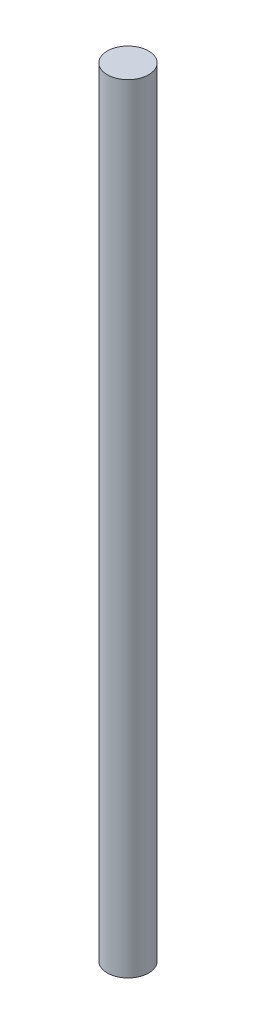
SolidWorks part; units mm, degrees
ref_plane "Front Plane" through (0, 0, 0) normal (0, 0, 1) x (1, 0, 0)
ref_plane "Top Plane" through (0, 0, 0) normal (0, 1, 0) x (1, 0, 0)
ref_plane "Right Plane" through (0, 0, 0) normal (1, 0, 0) x (0, 0, -1)
sketch "Sketch1" plane through (0, 0, 0) normal (0, 1, 0) x (1, 0, 0)
  circle A0 centre (0, 0) radius 0.7937
  dimension "D1" = 1.5875
extrude "Boss-Extrude1" add sketch "Sketch1" along normal blind 29.9085 contours A0
